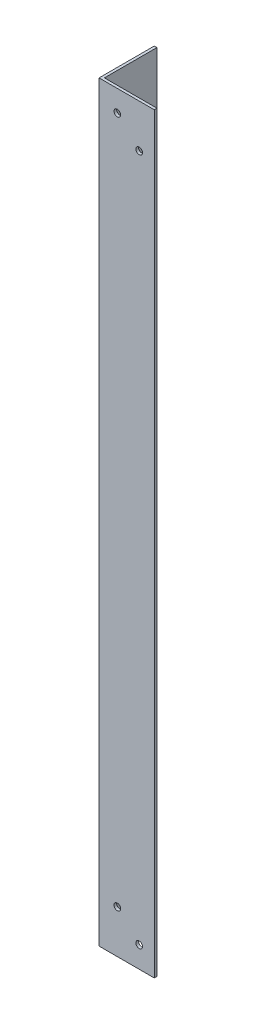
SolidWorks part; units mm, degrees
ref_plane "Front" through (0, 0, 0) normal (0, 0, 1) x (1, 0, 0)
ref_plane "Top" through (0, 0, 0) normal (0, 1, 0) x (1, 0, 0)
ref_plane "Right" through (0, 0, 0) normal (1, 0, 0) x (0, 0, -1)
sketch "Эскиз1" plane through (0, 0, 0) normal (0, 1, 0) x (1, 0, 0)
  line L0 (0, 0) -> (0, 25)
  line L1 (0, 0) -> (25, 0)
  line L2 (25, 0) -> (25, 1.2)
  line L3 (0, 25) -> (1.2, 25)
  line L4 (1.2, 25) -> (1.2, 1.2)
  line L5 (1.2, 1.2) -> (25, 1.2)
extrude "Бобышка-Вытянуть1" add sketch "Эскиз1" along normal blind 340.5
sketch "Эскиз2" plane through (0, 0, -1.2) normal (0, 0, -1) x (-1, 0, 0)
  line L0 (-18.17, 320.9635) -> (-8.2705, 330.863) construction
  line L1 (-1.2, 340.5) -> (-1.2, 0) construction
  line L2 (-13.2203, 325.9133) -> (-18.17, 325.9133) construction
  line L9 (-1.2, 170.25) -> (-25, 170.25) construction
  line L10 (-25, 340.5) -> (-25, 0) construction
  circle A4 centre (-8.2705, 330.863) radius 1.5
  circle A5 centre (-18.17, 320.9635) radius 1.5
  circle A8 centre (-8.2705, 19.5365) radius 1.5
  circle A9 centre (-18.17, 9.637) radius 1.5
extrude "Вырез-Вытянуть1" cut sketch "Эскиз2" against normal through all
